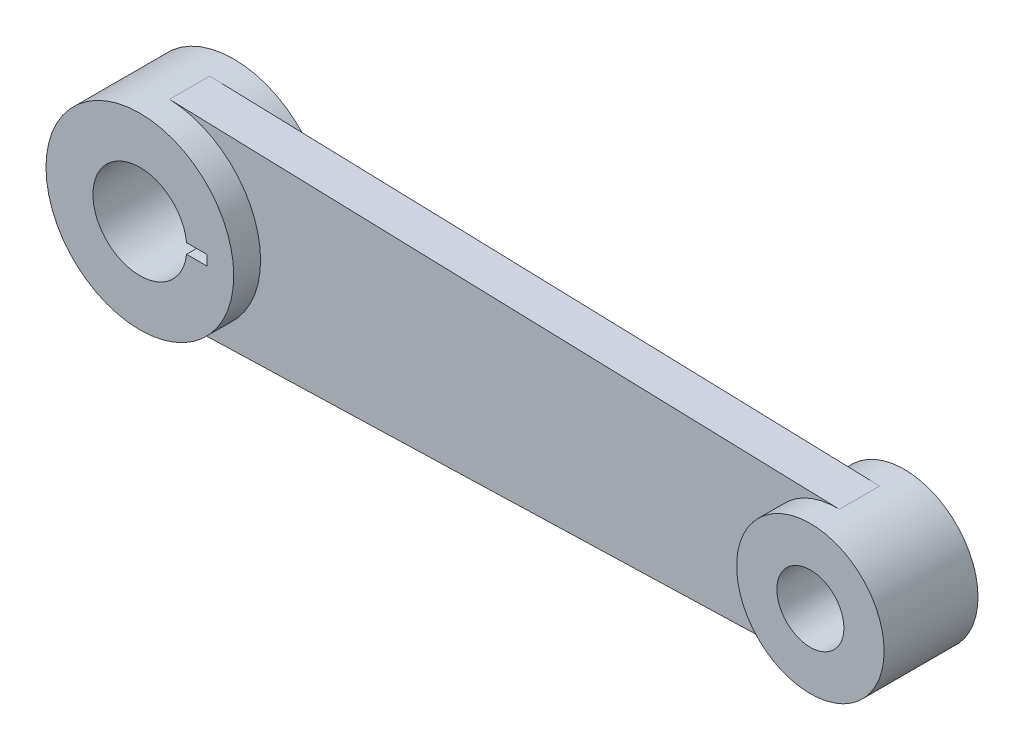
SolidWorks part; units mm, degrees
ref_plane "前视基准面" through (0, 0, 0) normal (0, 0, 1) x (1, 0, 0)
ref_plane "上视基准面" through (0, 0, 0) normal (0, 1, 0) x (1, 0, 0)
ref_plane "右视基准面" through (0, 0, 0) normal (1, 0, 0) x (0, 0, -1)
sketch "草图1" plane through (0, 0, 0) normal (0, 0, 1) x (1, 0, 0)
  line L0 (-37.5291, 0) -> (52.1957, 0) construction
  line L1 (-26.7835, 13.9937) -> (73.1265, 10.995)
  line L2 (73.1265, -10.995) -> (-26.7835, -13.9937)
  arc A0 (73.1265, 10.995) -> (73.1265, -10.995) centre (72.7965, 0) cw
  arc A1 (-26.7835, -13.9937) -> (-26.7835, 13.9937) centre (-27.2035, 0) cw
  point P9 (0, 0)
  point P10 (0, 0)
  dimension "D1" = 14
  dimension "D2" = 11
  dimension "D3" = 100
extrude "凸台-拉伸1" add sketch "草图1" along normal blind 6
ref_plane "基准面2" through (0, 0, 3) normal (0, 0, 1) x (1, 0, 0)
sketch "草图3" plane through (0, 0, 3) normal (0, 0, 1) x (1, 0, 0)
  circle A0 centre (-27.2035, 0) radius 14
  circle A1 centre (72.7965, 0) radius 11
extrude "凸台-拉伸3" add sketch "草图3" along normal mid plane 14
ref_plane "基准面3" through (0, 0, 10) normal (0, 0, 1) x (1, 0, 0)
sketch "草图4" plane through (0, 0, 10) normal (0, 0, 1) x (1, 0, 0)
  line L0 (67.7965, 0) -> (1140.3099, 0)
  line L1 (-20.2438, 0.75) -> (-17.2035, 0.75)
  line L2 (-20.2438, -0.75) -> (-17.2035, -0.75)
  line L3 (-17.2035, 0.75) -> (-17.2035, -0.75)
  line L4 (-1017.2035, 0.75) -> (1140.3099, 0.75) construction
  line L5 (-1017.2035, -0.75) -> (1140.3099, -0.75) construction
  line L6 (-1017.2035, 0) -> (1140.3099, 0) construction
  line L7 (67.853, 0.75) -> (1140.3099, 0.75)
  line L8 (67.853, -0.75) -> (1140.3099, -0.75)
  arc A0 (-20.2438, 0.75) -> (-20.2438, -0.75) centre (-27.2035, 0) ccw
  circle A1 centre (72.7965, 0) radius 5
  dimension "D1" = 14
  dimension "D2" = 10
  dimension "D3" = 0.75
  dimension "D5" = 10
  dimension "D4" = 0.75
extrude "切除-拉伸1" cut sketch "草图4" against normal through all
